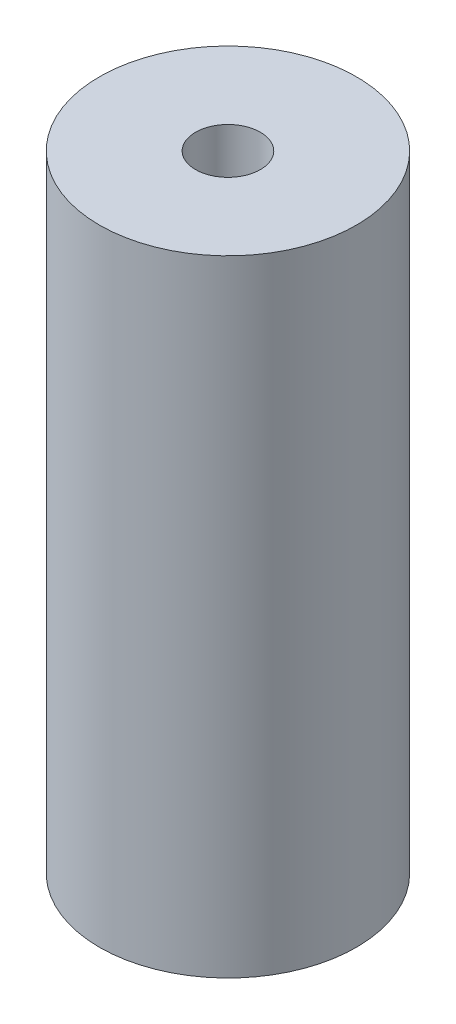
SolidWorks part; units mm, degrees
ref_plane "Front Plane" through (0, 0, 0) normal (0, 0, 1) x (1, 0, 0)
ref_plane "Top Plane" through (0, 0, 0) normal (0, 1, 0) x (1, 0, 0)
ref_plane "Right Plane" through (0, 0, 0) normal (1, 0, 0) x (0, 0, -1)
sketch "Sketch1" plane through (0, 0, 0) normal (0, 1, 0) x (1, 0, 0)
  circle A0 centre (0, 0) radius 11.3
  dimension "D1" = 22.6
extrude "Boss-Extrude1" add sketch "Sketch1" along normal blind 55
sketch "Sketch2" plane through (0, 55, 0) normal (0, 1, 0) x (1, 0, 0)
  circle A0 centre (0, 0) radius 2.85
  dimension "D1" = 5.7
extrude "Cut-Extrude1" cut sketch "Sketch2" against normal blind 110
